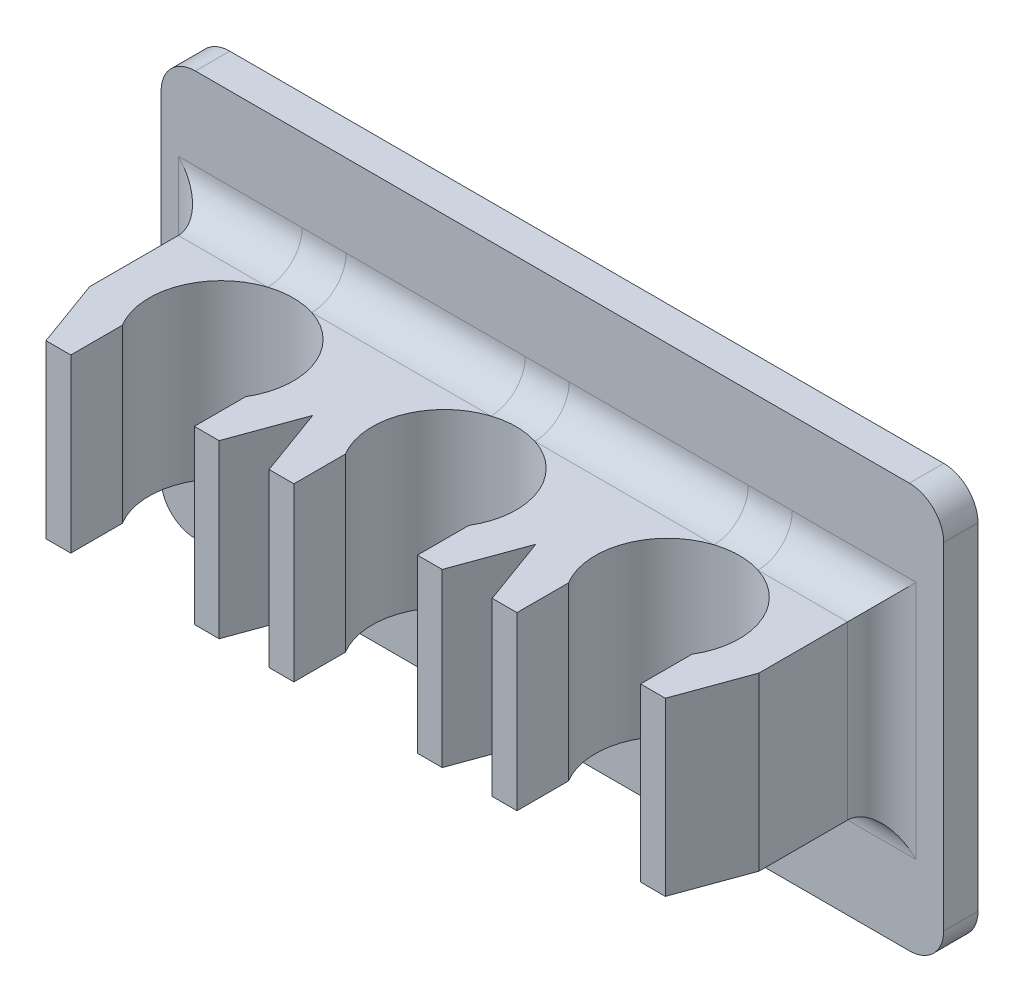
SolidWorks part; units mm, degrees
ref_plane "Front Plane" through (0, 0, 0) normal (0, 0, 1) x (1, 0, 0)
ref_plane "Top Plane" through (0, 0, 0) normal (0, 1, 0) x (1, 0, 0)
ref_plane "Right Plane" through (0, 0, 0) normal (1, 0, 0) x (0, 0, -1)
sketch "Sketch1" plane through (0, 0, 0) normal (0, 0, 1) x (1, 0, 0)
  line L1 (11.4, -5.9) -> (-11.4, -5.9)
  line L2 (11.4, -5.9) -> (11.4, 5.9)
  line L3 (11.4, 5.9) -> (-11.4, 5.9)
  line L4 (-11.4, -5.9) -> (-11.4, 5.9)
  line L5 (11.4, -5.9) -> (-11.4, 5.9) construction
  line L6 (11.4, 5.9) -> (-11.4, -5.9) construction
  point P0 (0, 0)
  dimension "D1" = 11.8
  dimension "D2" = 22.8
extrude "Boss-Extrude1" add sketch "Sketch1" along normal blind 1
sketch "Sketch3" plane through (0, 0, 0) normal (0, -1, 0) x (1, 0, 0)
  line L0 (-9.9, 1) -> (-9.9, 4.5817)
  line L1 (-11.4, 1) -> (11.4, 1) construction
  line L2 (-9.1721, 6.5817) -> (-8.45, 6.5817)
  line L3 (-8.45, 6.5817) -> (-8.45, 5.0817)
  line L4 (-6.65, 4) -> (-6.65, 1) construction
  line L5 (-4.85, 6.5817) -> (-4.85, 5.0817)
  line L8 (-11.4, 1) -> (-11.4, 0) construction
  line L9 (-9.9, 1) -> (-3.4, 1)
  line L10 (-9.9, 4.5817) -> (-9.1721, 6.5817)
  line L11 (-3.4, 1) -> (-3.4, 4.5817)
  line L12 (-3.4, 4.5817) -> (-4.1279, 6.5817)
  line L13 (-4.1279, 6.5817) -> (-4.85, 6.5817)
  arc A0 (-8.45, 5.0817) -> (-4.85, 5.0817) centre (-6.65, 4) ccw
  arc A1 (-4.85, 5.0817) -> (-8.45, 5.0817) centre (-6.65, 4) ccw construction
  point P4 (-9.9, 6.5817)
  dimension "D1" = 4.2
  dimension "D2" = 3.6
  dimension "D3" = 1.5
  dimension "D4" = 6.5
  dimension "D5" = 3
  dimension "D6" = 1.5
  dimension "D7" = 2
  dimension "D8" = 20
extrude "Boss-Extrude2" add sketch "Sketch3" along normal mid plane 5
pattern_linear "LPattern2" count 3 spacing 6.5 along (1, 0, 0) of "Boss-Extrude2"
fillet "Fillet1" radius 1 4 edges at (11.4, 5.9, 0.5) (11.4, -5.9, 0.5) (-11.4, 5.9, 0.5) (-11.4, -5.9, 0.5)
fillet "Fillet2" radius 1 4 edges at (9.6, 0, 1) (-9.9, 0, 1) (-0.15, 2.5, 1) (-0.15, -2.5, 1)
